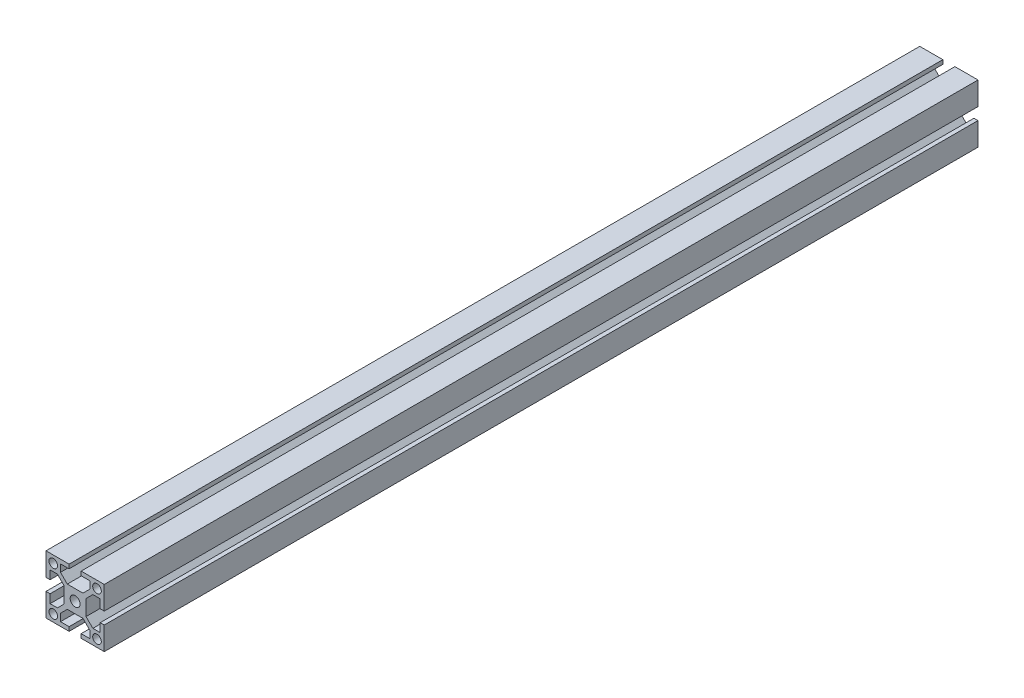
SolidWorks part; units mm, degrees
ref_plane "前视基准面" through (0, 0, 0) normal (0, 0, 1) x (1, 0, 0)
ref_plane "上视基准面" through (0, 0, 0) normal (0, 1, 0) x (1, 0, 0)
ref_plane "右视基准面" through (0, 0, 0) normal (1, 0, 0) x (0, 0, -1)
sketch "草图1" plane through (0, 0, 0) normal (0, 0, 1) x (1, 0, 0)
  line L0 (0.0875, -0.2472) -> (394.7541, -0.2472) construction
  line L1 (-113.0431, 0) -> (141.4939, 0) construction
  line L2 (0, -117.7654) -> (0, 112.0789) construction
  line L3 (0, 0) -> (37.1582, 37.1582) construction
  line L4 (-5.3787, -7.5) -> (5.3787, -7.5)
  line L5 (-7.5, -5.3787) -> (-7.5, 5.3787)
  line L6 (-5.3787, 7.5) -> (5.3787, 7.5)
  line L7 (7.5, -5.3787) -> (7.5, 5.3787)
  line L8 (-7.5, -7.5) -> (7.5, 7.5) construction
  line L9 (-7.5, 7.5) -> (7.5, -7.5) construction
  line L10 (7.5, 5.3787) -> (12.1713, 10.05)
  line L11 (20, 20) -> (20, 4.15)
  line L12 (20, 20) -> (4.15, 20)
  line L13 (20, 4.15) -> (17.2, 4.15)
  line L14 (4.15, 20) -> (4.15, 17.2)
  line L15 (17.2, 4.15) -> (17.2, 10.05)
  line L16 (12.1713, 10.05) -> (17.2, 10.05)
  line L17 (4.15, 17.2) -> (10.05, 17.2)
  line L18 (10.05, 12.1713) -> (10.05, 17.2)
  line L19 (5.3787, 7.5) -> (10.05, 12.1713)
  line L20 (-5.3787, 7.5) -> (-10.05, 12.1713)
  line L21 (-10.05, 12.1713) -> (-10.05, 17.2)
  line L22 (-4.15, 17.2) -> (-10.05, 17.2)
  line L23 (-12.1713, 10.05) -> (-17.2, 10.05)
  line L24 (-17.2, 4.15) -> (-17.2, 10.05)
  line L25 (-4.15, 20) -> (-4.15, 17.2)
  line L26 (-20, 4.15) -> (-17.2, 4.15)
  line L27 (-20, 20) -> (-4.15, 20)
  line L28 (-20, 20) -> (-20, 4.15)
  line L29 (-7.5, 5.3787) -> (-12.1713, 10.05)
  line L30 (-7.5, -5.3787) -> (-12.1713, -10.05)
  line L31 (-20, -20) -> (-20, -4.15)
  line L32 (-20, -20) -> (-4.15, -20)
  line L33 (-20, -4.15) -> (-17.2, -4.15)
  line L34 (-4.15, -20) -> (-4.15, -17.2)
  line L35 (-17.2, -4.15) -> (-17.2, -10.05)
  line L36 (-12.1713, -10.05) -> (-17.2, -10.05)
  line L37 (-4.15, -17.2) -> (-10.05, -17.2)
  line L38 (-10.05, -12.1713) -> (-10.05, -17.2)
  line L39 (-5.3787, -7.5) -> (-10.05, -12.1713)
  line L40 (5.3787, -7.5) -> (10.05, -12.1713)
  line L41 (10.05, -12.1713) -> (10.05, -17.2)
  line L42 (4.15, -17.2) -> (10.05, -17.2)
  line L43 (12.1713, -10.05) -> (17.2, -10.05)
  line L44 (17.2, -4.15) -> (17.2, -10.05)
  line L45 (4.15, -20) -> (4.15, -17.2)
  line L46 (20, -4.15) -> (17.2, -4.15)
  line L47 (20, -20) -> (4.15, -20)
  line L48 (20, -20) -> (20, -4.15)
  line L49 (7.5, -5.3787) -> (12.1713, -10.05)
  circle A0 centre (0, 0) radius 3.4
  circle A1 centre (15.025, 15.025) radius 2.95
  circle A2 centre (-15.025, 15.025) radius 2.95
  circle A3 centre (-15.025, -15.025) radius 2.95
  circle A4 centre (15.025, -15.025) radius 2.95
  dimension "D1" = 6.8
  dimension "D2" = 15
  dimension "D5" = 5.9
  dimension "D3" = 15
  dimension "D4" = 7.5
  dimension "D6" = 15.025
  dimension "D7" = 20
  dimension "D8" = 20
  dimension "D9" = 4.15
  dimension "D10" = 3
  dimension "D11" = 2.8
  dimension "D12" = 10.05
extrude "凸台-拉伸1" add sketch "草图1" along normal blind 600
